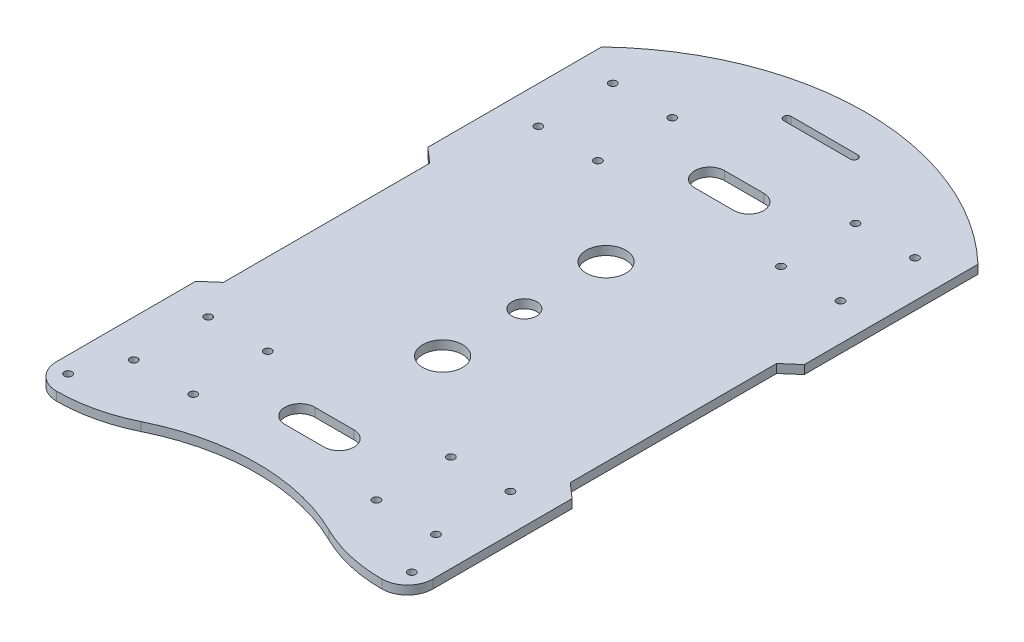
SolidWorks part; units mm, degrees
material "Aleación 6061"
ref_plane "Alzado" through (0, 0, 0) normal (0, 0, 1) x (1, 0, 0)
ref_plane "Planta" through (0, 0, 0) normal (0, 1, 0) x (1, 0, 0)
ref_plane "Vista lateral" through (0, 0, 0) normal (1, 0, 0) x (0, 0, -1)
sketch "Croquis1" plane through (0, 0, 0) normal (0, 1, 0) x (1, 0, 0)
  line L0 (0, 0) -> (-69.88, 0) construction
  line L1 (-7.895, -82.555) -> (7.895, -82.555) construction
  line L2 (-7.895, -88.57) -> (7.895, -88.57)
  line L3 (-7.895, -76.54) -> (7.895, -76.54)
  line L5 (0, 137.38) -> (0, -107.7306) construction
  line L6 (0, 24.92) -> (0, -24.96) construction
  line L7 (0, -40.96) -> (0, -76.58) construction
  line L8 (-7.895, 82.555) -> (7.895, 82.555) construction
  line L9 (-7.895, 88.57) -> (7.895, 88.57)
  line L10 (-7.895, 76.54) -> (7.895, 76.54)
  line L11 (0, 40.92) -> (0, 76.54) construction
  line L12 (0, 117.93) -> (0, 88.57) construction
  line L13 (0, 120.93) -> (0, 137.38) construction
  line L17 (-13.415, 119.43) -> (13.415, 119.43) construction
  line L18 (-13.415, 120.93) -> (13.415, 120.93)
  line L19 (-13.415, 117.93) -> (13.415, 117.93)
  line L23 (-75.83, 106.96) -> (-75.83, 36.96)
  line L24 (75.83, 106.96) -> (75.83, 36.96)
  line L28 (75.83, 36.96) -> (69.88, 31.76)
  line L29 (69.88, 31.76) -> (69.88, -51.39)
  line L32 (-69.88, 31.76) -> (-69.88, -51.39)
  line L36 (69.88, -51.39) -> (75.83, -56.59)
  line L39 (-69.88, -51.39) -> (-75.83, -56.59)
  line L47 (75.83, -56.59) -> (75.83, -112.67)
  line L48 (-69.88, 31.76) -> (-75.83, 36.96)
  line L50 (-75.83, -56.59) -> (-75.83, -112.67)
  arc A0 (-7.895, 88.57) -> (-7.895, 76.54) centre (-7.895, 82.555) ccw
  arc A1 (7.895, 76.54) -> (7.895, 88.57) centre (7.895, 82.555) ccw
  circle A2 centre (0, 32.92) radius 8
  arc A3 (-13.415, 120.93) -> (-13.415, 117.93) centre (-13.415, 119.43) ccw
  arc A4 (13.415, 117.93) -> (13.415, 120.93) centre (13.415, 119.43) ccw
  arc A5 (-75.83, 106.96) -> (75.83, 106.96) centre (0, 27.6567) cw
  arc A9 (-37.8413, -116.5308) -> (37.8413, -116.5308) centre (0, -193.4905) cw
  arc A11 (65.53, -122.97) -> (75.83, -112.67) centre (65.53, -112.67) ccw
  arc A12 (-65.53, -122.97) -> (-75.83, -112.67) centre (-65.53, -112.67) cw
  arc A13 (65.53, -122.97) -> (37.8413, -116.5308) centre (65.53, -60.2192) cw
  arc A14 (-65.53, -122.97) -> (-37.8413, -116.5308) centre (-65.53, -60.2192) ccw
  circle A15 centre (69.23, -114.59) radius 1.55
  arc A16 (-7.895, -88.57) -> (-7.895, -76.54) centre (-7.895, -82.555) cw
  arc A17 (7.895, -76.54) -> (7.895, -88.57) centre (7.895, -82.555) cw
  circle A18 centre (0, -32.92) radius 8
  circle A19 centre (-69.23, -114.59) radius 1.55
  point P13 (0, 82.555)
  point P27 (0, 119.43)
  point P35 (0, -82.555)
  point P52 (0, -88.57)
  dimension "D5" = 83.15
  dimension "D6" = 56.08
  dimension "D7" = 5.2
  dimension "D10" = 62.7508
  dimension "D11" = 24.92
  dimension "D12" = 16
  dimension "D14" = 6.015
  dimension "D15" = 19.1606
  dimension "D17" = 29.36
  dimension "D1" = 85.7598
  dimension "D3" = 109.7233
  dimension "D9" = 10.3
  dimension "D18" = 1.5
  dimension "D22" = 3.1
  dimension "D2" = 151.66
  dimension "D4" = 70
  dimension "D8" = 5.95
  dimension "D13" = 15.79
  dimension "D16" = 35.62
  dimension "D19" = 26.83
  dimension "D20" = 16.45
  dimension "D21" = 69.88
  dimension "D23" = 58
  dimension "D24" = 6.6
extrude "Saliente-Extruir1" add sketch "Croquis1" along normal blind 3.5
sketch "Croquis2" plane through (0, 3.5, 0) normal (0, 1, 0) x (1, 0, 0)
  line L1 (-60.88, 66.51) -> (-62.43, 66.51) construction
  line L2 (-75.83, 106.96) -> (-75.83, 36.96) construction
  line L3 (-60.88, 66.51) -> (-60.88, 64.96) construction
  line L4 (0, 0) -> (0, 146.1149) construction
  line L5 (0, 0) -> (-151.1961, 0) construction
  circle A0 centre (-60.88, 66.51) radius 1.55
  circle A1 centre (-60.88, 96.51) radius 1.55
  circle A2 centre (-36.88, 96.51) radius 1.55
  circle A3 centre (-36.88, 66.51) radius 1.55
  circle A4 centre (60.88, 66.51) radius 1.55
  circle A5 centre (36.88, 66.51) radius 1.55
  circle A6 centre (36.88, 96.51) radius 1.55
  circle A7 centre (60.88, 96.51) radius 1.55
  circle A8 centre (60.88, -96.51) radius 1.55
  circle A9 centre (36.88, -96.51) radius 1.55
  circle A10 centre (36.88, -66.51) radius 1.55
  circle A11 centre (60.88, -66.51) radius 1.55
  circle A12 centre (-36.88, -66.51) radius 1.55
  circle A13 centre (-36.88, -96.51) radius 1.55
  circle A14 centre (-60.88, -96.51) radius 1.55
  circle A15 centre (-60.88, -66.51) radius 1.55
  dimension "D1" = 3.1
  dimension "D4" = 30
  dimension "D5" = 24
  dimension "D2" = 13.4
  dimension "D3" = 28
extrude "Cortar-Extruir1" cut sketch "Croquis2" against normal through all
sketch "Croquis3" plane through (0, 3.5, 0) normal (0, 1, 0) x (1, 0, 0)
  circle A0 centre (0, 0) radius 5
  dimension "D1" = 10
extrude "Cortar-Extruir2" cut sketch "Croquis3" against normal blind 10
